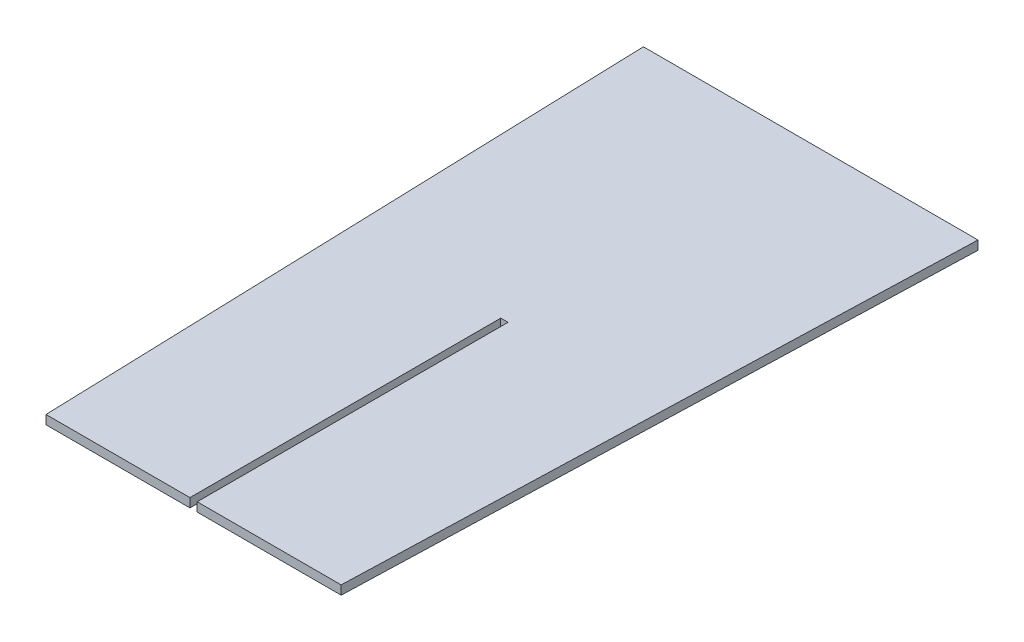
SolidWorks part; units mm, degrees
ref_plane "Front Plane" through (0, 0, 0) normal (0, 0, 1) x (1, 0, 0)
ref_plane "Top Plane" through (0, 0, 0) normal (0, 1, 0) x (1, 0, 0)
ref_plane "Right Plane" through (0, 0, 0) normal (1, 0, 0) x (0, 0, -1)
sketch "Sketch1" plane through (0, 0, 0) normal (0, 1, 0) x (1, 0, 0)
  line L0 (262.6692, 448.3604) -> (367.4633, 448.3604)
  line L1 (276.6773, 10.2104) -> (378.8726, 10.2104)
  line L2 (378.8726, 10.2104) -> (378.8726, 230.8729)
  line L3 (262.6692, 448.3604) -> (276.6773, 10.2104)
  line L4 (500.2354, 448.3604) -> (486.2273, 10.2104)
  line L5 (367.4633, 448.3604) -> (367.4633, 430.8979)
  line L6 (367.4633, 430.8979) -> (395.4414, 430.8979)
  line L7 (395.4414, 448.3604) -> (395.4414, 430.8979)
  line L8 (384.032, 10.2104) -> (384.032, 230.8729)
  line L9 (378.8726, 230.8729) -> (384.032, 230.8729)
  line L10 (384.032, 10.2104) -> (486.2273, 10.2104)
  line L11 (395.4414, 448.3604) -> (500.2354, 448.3604)
extrude "Boss-Extrude1" add sketch "Sketch1" against normal blind 6.35
sketch "Sketch2" plane through (0, 0, 0) normal (0, 1, 0) x (1, 0, 0)
  line L0 (367.4633, 448.3604) -> (395.4414, 448.3604)
  line L1 (395.4414, 448.3604) -> (395.4414, 430.8979)
  line L2 (395.4414, 430.8979) -> (367.4633, 430.8979)
  line L3 (367.4633, 430.8979) -> (367.4633, 448.3604)
extrude "Boss-Extrude2" add sketch "Sketch2" against normal blind 6.35
